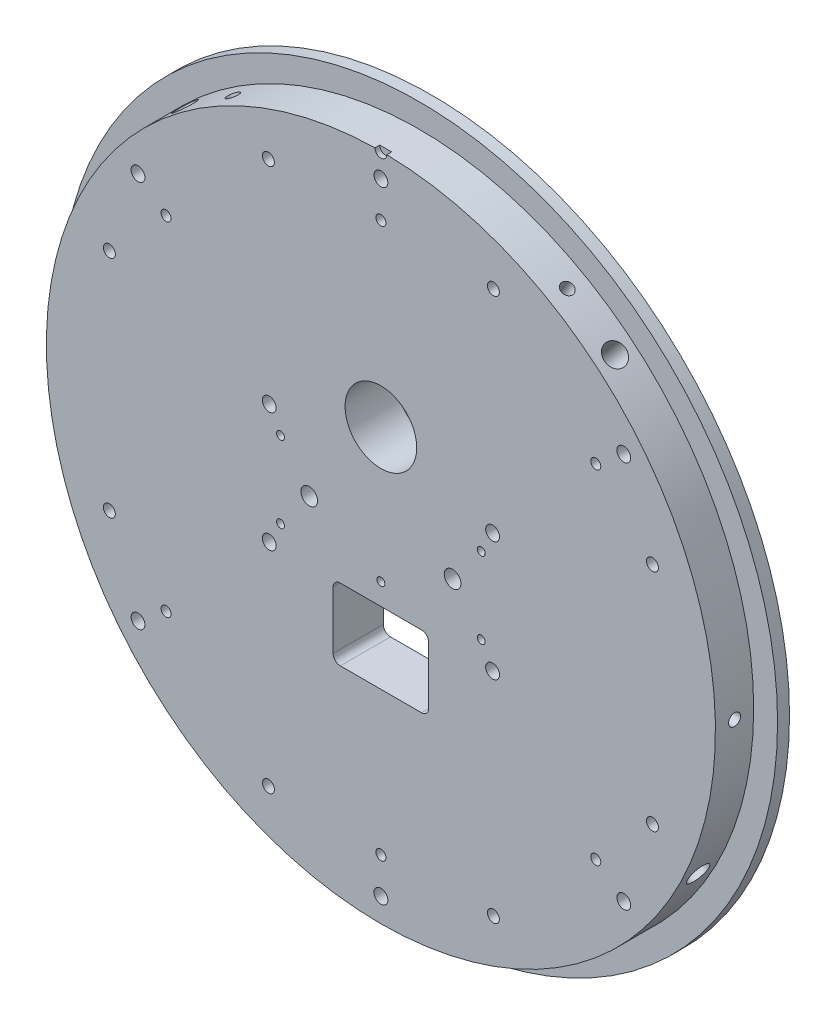
SolidWorks part; units mm, degrees
material "2017-T4"
ref_plane "正面" through (0, 0, 0) normal (0, 0, 1) x (1, 0, 0)
ref_plane "平面" through (0, 0, 0) normal (0, 1, 0) x (1, 0, 0)
ref_plane "右側面" through (0, 0, 0) normal (1, 0, 0) x (0, 0, -1)
ref_axis "中心軸" through (0, 0, -1.05) along (0, 0, 1)
sketch "ｽｹｯﾁ1" plane through (0, 0, 0) normal (0, 0, 1) x (1, 0, 0)
  circle A0 centre (0, 0) radius 150
  dimension "D1" = 300
extrude "ﾎﾞｽ - 押し出し1" add sketch "ｽｹｯﾁ1" along normal blind 5
sketch "ｽｹｯﾁ2" plane through (0, 0, 5) normal (0, 0, 1) x (1, 0, 0)
  circle A0 centre (0, 0) radius 140
  dimension "D1" = 280
extrude "ﾎﾞｽ - 押し出し2" add sketch "ｽｹｯﾁ2" along normal blind 16 contours A0
sketch "ｽｹｯﾁ3" plane through (0, 0, 0) normal (0, 0, -1) x (-1, 0, 0)
  line L1 (-20, -55) -> (20, -55)
  line L2 (-20, -55) -> (-20, -25)
  line L3 (-20, -25) -> (20, -25)
  line L4 (20, -55) -> (20, -25)
  line L5 (-20, -55) -> (20, -25) construction
  line L6 (-20, -25) -> (20, -55) construction
  circle A0 centre (0, 40) radius 15
  point P2 (0, -40)
  dimension "D1" = 30
  dimension "D2" = 40
  dimension "D3" = 40
  dimension "D4" = 30
  dimension "D5" = 55
extrude "ｶｯﾄ - 押し出し1" cut sketch "ｽｹｯﾁ3" against normal through all
fillet "ﾌｨﾚｯﾄ2" radius 3 4 edges at (20, -55, 10.5) (20, -25, 10.5) (-20, -25, 10.5) (-20, -55, 10.5)
sketch "ｽｹｯﾁ5" plane through (0, 0, 0) normal (0, 0, -1) x (-1, 0, 0)
  circle A0 centre (0, 0) radius 130
  point P3 (0, 130)
  point P4 (101.6401, 81.0511)
  point P5 (-101.6401, 81.0511)
  point P6 (-101.6401, -81.0511)
  point P7 (101.6401, -81.0511)
  point P8 (0, -130)
  dimension "D1" = 260
  dimension "D2" = 51.43
  dimension "D3" = 51.43
  dimension "D4" = 51.43
  dimension "D5" = 51.43
hole_wizard "M5 穴付きねじ用座ぐり穴1" positions "3Dｽｹｯﾁ1" profile "ｽｹｯﾁ4" counterbore size "M5" standard "JIS" end condition through all
sketch3d "3Dｽｹｯﾁ1"
  point P0 (0, 130, 0)
  point P2 (-101.6401, 81.0511, 0)
  point P4 (101.6401, 81.0511, 0)
  point P6 (101.6401, -81.0511, 0)
  point P8 (0, -130, 0)
  point P10 (-101.6401, -81.0511, 0)
sketch "ｽｹｯﾁ4" plane through (0, 130, 0) normal (1, 0, 0) x (0, 1, 0)
  line L0 (0, 0) -> (0, 21)
  line L1 (0, 21) -> (2.9, 21)
  line L3 (2.9, 21) -> (2.9, 8)
  line L4 (2.9, 8) -> (5, 8)
  line L5 (5, 8) -> (5, 0)
  line L7 (5, 0) -> (0, 0)
  line L11 (0, -6.35) -> (0, 107.95) construction
  dimension "通し穴の直径" = 5.8
  dimension "通し穴の深さ" = 21
  dimension "座ぐり穴の直径" = 10
  dimension "座ぐり穴の深さ" = 8
sketch "ｽｹｯﾁ7" plane through (0, 0, 0) normal (0, 0, -1) x (-1, 0, 0)
  point P0 (-30, 0)
  point P1 (30, 0)
  dimension "D1" = 30
  dimension "D2" = 30
hole_wizard "M6 穴付きねじ用座ぐり穴1" positions "3Dｽｹｯﾁ2" profile "ｽｹｯﾁ6" counterbore size "M6" standard "JIS" end condition through all
sketch3d "3Dｽｹｯﾁ2"
  point P0 (30, 0, 0)
  point P2 (-30, 0, 0)
sketch "ｽｹｯﾁ6" plane through (30, 0, 0) normal (1, 0, 0) x (0, 1, 0)
  line L0 (0, 0) -> (0, 21)
  line L1 (0, 21) -> (3.5, 21)
  line L3 (3.5, 21) -> (3.5, 9)
  line L4 (3.5, 9) -> (5.5, 9)
  line L5 (5.5, 9) -> (5.5, 0)
  line L7 (5.5, 0) -> (0, 0)
  line L11 (0, -6.35) -> (0, 107.95) construction
  dimension "通し穴の直径" = 7
  dimension "通し穴の深さ" = 21
  dimension "座ぐり穴の直径" = 11
  dimension "座ぐり穴の深さ" = 9
sketch "ｽｹｯﾁ8" plane through (0, 0, 0) normal (0, 0, -1) x (-1, 0, 0)
  line L1 (-46.7333, -25) -> (46.7333, -25) construction
  line L2 (-46.7333, -25) -> (-46.7333, 25) construction
  line L3 (-46.7333, 25) -> (46.7333, 25) construction
  line L4 (46.7333, -25) -> (46.7333, 25) construction
  line L5 (-46.7333, -25) -> (46.7333, 25) construction
  line L6 (-46.7333, 25) -> (46.7333, -25) construction
  point P0 (0, 0)
  dimension "D1" = 50
  dimension "D2" = 53
hole_wizard "M5 穴付きねじ用座ぐり穴2" positions "3Dｽｹｯﾁ3" profile "ｽｹｯﾁ9" counterbore size "M5" standard "JIS" end condition through all
sketch3d "3Dｽｹｯﾁ3"
  point P0 (46.7333, 25, 0)
  point P3 (46.7333, -25, 0)
  point P6 (-46.7333, 25, 0)
  point P9 (-46.7333, -25, 0)
sketch "ｽｹｯﾁ9" plane through (46.7333, 25, 0) normal (1, 0, 0) x (0, 1, 0)
  line L0 (0, 0) -> (0, 21)
  line L1 (0, 21) -> (2.9, 21)
  line L3 (2.9, 21) -> (2.9, 8)
  line L4 (2.9, 8) -> (5, 8)
  line L5 (5, 8) -> (5, 0)
  line L7 (5, 0) -> (0, 0)
  line L11 (0, -6.35) -> (0, 107.95) construction
  dimension "通し穴の直径" = 5.8
  dimension "通し穴の深さ" = 21
  dimension "座ぐり穴の直径" = 10
  dimension "座ぐり穴の深さ" = 8
sketch "ｽｹｯﾁ10" plane through (0, 0, 0) normal (0, 0, -1) x (-1, 0, 0)
  line L1 (-42, -16) -> (42, -16)
  line L2 (-42, -16) -> (-42, 16)
  line L3 (-42, 16) -> (42, 16)
  line L4 (42, -16) -> (42, 16)
  line L5 (-42, -16) -> (42, 16) construction
  line L6 (-42, 16) -> (42, -16) construction
  point P0 (0, 0)
  point P5 (0, -16)
  dimension "D1" = 84
  dimension "D2" = 32
hole_wizard "M4x0.7 ねじ穴1" positions "3Dｽｹｯﾁ4" profile "ｽｹｯﾁ11" tap size "M4x0.7" standard "JIS" end condition through all
sketch3d "3Dｽｹｯﾁ4"
  point P0 (42, 16, 0)
  point P3 (-42, 16, 0)
  point P6 (-42, -16, 0)
  point P9 (0, -16, 0)
  point P12 (42, -16, 0)
sketch "ｽｹｯﾁ11" plane through (42, 16, 0) normal (1, 0, 0) x (0, 1, 0)
  line L0 (0, 0) -> (0, 21)
  line L1 (0, 21) -> (1.65, 21)
  line L2 (1.65, 21) -> (1.65, 0)
  line L5 (1.65, 0) -> (0, 0)
  line L11 (0, -6.35) -> (0, 107.95) construction
  dimension "次ｻｰﾌｪｽまでのねじ下穴ﾄﾞﾘﾙ直径" = 3.3
  dimension "次ｻｰﾌｪｽまでのねじ下穴ﾄﾞﾘﾙの深さ" = 21
cosmetic thread "穴のねじ山1" parameters "D2"=4
cosmetic thread "穴のねじ山2" parameters "D2"=4
cosmetic thread "穴のねじ山3" parameters "D2"=4
cosmetic thread "穴のねじ山4" parameters "D2"=4
cosmetic thread "穴のねじ山5" parameters "D2"=4
sketch "ｽｹｯﾁ12" plane through (0, 0, 0) normal (0, 0, -1) x (-1, 0, 0)
  line L0 (0, 0) -> (212.6109, 0) construction
  line L1 (0, 0) -> (198.3068, 82.1414) construction
  point P3 (113.6372, 47.0701)
  dimension "D1" = 123
  dimension "D2" = 22.5
hole_wizard "M6x1.0 ねじ穴1" positions "3Dｽｹｯﾁ5" profile "ｽｹｯﾁ13" tap size "M6x1.0" standard "JIS" end condition through all
sketch3d "3Dｽｹｯﾁ5"
  point P0 (-113.6372, 47.0701, 0)
sketch "ｽｹｯﾁ13" plane through (-113.6372, 47.0701, 0) normal (1, 0, 0) x (0, 1, 0)
  line L0 (0, 0) -> (0, 21)
  line L1 (0, 21) -> (2.5, 21)
  line L2 (2.5, 21) -> (2.5, 0)
  line L5 (2.5, 0) -> (0, 0)
  line L11 (0, -6.35) -> (0, 107.95) construction
  dimension "次ｻｰﾌｪｽまでのねじ下穴ﾄﾞﾘﾙ直径" = 5
  dimension "次ｻｰﾌｪｽまでのねじ下穴ﾄﾞﾘﾙの深さ" = 21
cosmetic thread "穴のねじ山6" parameters "D2"=6
pattern_circular "円形ﾊﾟﾀｰﾝ1" count 8 over 360 about axis through (0, 0, 0) along (0, 0, 1) of "M6x1.0 ねじ穴1"
sketch "ｽｹｯﾁ14" plane through (0, 0, 21) normal (0, 0, -1) x (-1, 0, 0)
  circle A0 centre (0, 140) radius 2.5
  circle A2 centre (0, 0) radius 140 construction
  dimension "D1" = 5
extrude "ｶｯﾄ - 押し出し2" cut sketch "ｽｹｯﾁ14" along normal blind 2
sketch "ｽｹｯﾁ16" plane through (0, 0, 0) normal (0, 0, 1) x (1, 0, 0)
  circle A0 centre (0, 0) radius 115
  point P3 (0, 115)
  point P4 (89.9124, 71.6991)
  point P5 (-89.9124, 71.6991)
  point P6 (-89.9124, -71.6991)
  point P7 (89.9124, -71.6991)
  point P8 (0, -115)
  dimension "D1" = 230
  dimension "D2" = 51.43
  dimension "D3" = 51.43
  dimension "D4" = 51.43
  dimension "D5" = 51.43
hole_wizard "M5x0.8 ねじ穴1" positions "3Dｽｹｯﾁ6" profile "ｽｹｯﾁ17" tap size "M5x0.8" standard "JIS" end condition through all
sketch3d "3Dｽｹｯﾁ6"
  point P0 (-89.9124, 71.6991, 0)
  point P3 (-89.9124, 71.6991, 0)
  point P5 (-89.9124, -71.6991, 0)
  point P7 (0, -115, 0)
  point P9 (89.9124, -71.6991, 0)
  point P11 (89.9124, 71.6991, 0)
  point P13 (0, 115, 0)
sketch "ｽｹｯﾁ17" plane through (-89.9124, 71.6991, 0) normal (1, 0, 0) x (0, 1, 0)
  line L0 (0, 0) -> (0, 21)
  line L1 (0, 21) -> (2.1, 21)
  line L2 (2.1, 21) -> (2.1, 0)
  line L5 (2.1, 0) -> (0, 0)
  line L11 (0, -6.35) -> (0, 107.95) construction
  dimension "次ｻｰﾌｪｽまでのねじ下穴ﾄﾞﾘﾙ直径" = 4.2
  dimension "次ｻｰﾌｪｽまでのねじ下穴ﾄﾞﾘﾙの深さ" = 21
cosmetic thread "穴のねじ山7" parameters "D2"=5
cosmetic thread "穴のねじ山8" parameters "D2"=5
cosmetic thread "穴のねじ山9" parameters "D2"=5
cosmetic thread "穴のねじ山10" parameters "D2"=5
cosmetic thread "穴のねじ山11" parameters "D2"=5
cosmetic thread "穴のねじ山12" parameters "D2"=5
cosmetic thread "穴のねじ山13" parameters "D2"=5
ref_plane "平面1" through (0, 0, 13) normal (0, 0, 1) x (1, 0, 0)
sketch "ｽｹｯﾁ18" plane through (0, 0, 13) normal (0, 0, 1) x (1, 0, 0)
  circle A0 centre (0, 0) radius 140 construction
  circle A1 centre (0, 0) radius 140 construction
  point P0 (140, 0)
hole_wizard "M6x1.0 ねじ穴2" positions "3Dｽｹｯﾁ7" profile "ｽｹｯﾁ19" tap size "M6x1.0" standard "JIS"
sketch3d "3Dｽｹｯﾁ7"
  point P0 (140, 0, 13)
sketch "ｽｹｯﾁ19" plane through (140, 0, 13) normal (0, 1, 0) x (0, 0, -1)
  line L0 (0, 0) -> (0, 21.5022)
  line L1 (0, 21.5022) -> (2.5, 20)
  line L2 (2.5, 20) -> (2.5, 0)
  line L5 (2.5, 0) -> (0, 0)
  line L10 (0, 21.5022) -> (-2.5, 20) construction
  line L11 (0, -6.35) -> (0, 107.95) construction
  dimension "ねじ下穴ﾄﾞﾘﾙ直径" = 5
  dimension "ねじ下穴ﾄﾞﾘﾙの深さ" = 20
  dimension "ﾄﾞﾘﾙ角度" = 118
cosmetic thread "穴のねじ山14" parameters "D1"=12, "D2"=6
pattern_circular "円形ﾊﾟﾀｰﾝ2" count 6 over 360 about axis through (0, 0, -1.05) along (0, 0, 1) of "M6x1.0 ねじ穴2"
ref_plane "平面2" through (0, 0, 13) normal (0, 0, 1) x (1, 0, 0)
sketch "ｽｹｯﾁ20" plane through (0, 0, 13) normal (0, 0, 1) x (1, 0, 0)
  line L0 (0, 226.563) -> (0, -239.4482) construction
  line L1 (0, 0) -> (-89.9903, 107.2462) construction
  line L2 (0, 0) -> (89.9903, 107.2462) construction
  line L3 (0, 0) -> (124.7409, -63.5587) construction
  line L4 (0, 0) -> (-89.9903, -107.2462) construction
  circle A0 centre (0, 0) radius 140 construction
  arc A1 (-2.4999, 139.9777) -> (2.4999, 139.9777) centre (0, 0) ccw construction
  dimension "D1" = 40
  dimension "D2" = 40
  dimension "D3" = 63
  dimension "D4" = 40
hole_wizard "M10x1.0 ねじ穴1" positions "3Dｽｹｯﾁ8" profile "ｽｹｯﾁ21" tap size "M10x1.0" standard "JIS"
sketch3d "3Dｽｹｯﾁ8"
  point P0 (-89.9903, 107.2462, 13)
  point P2 (89.9903, 107.2462, 13)
  point P4 (124.7409, -63.5587, 13)
  point P6 (-89.9903, -107.2462, 13)
sketch "ｽｹｯﾁ21" plane through (-89.9903, 107.2462, 13) normal (0, 0, 1) x (-0.766, -0.6428, 0)
  line L0 (0, 0) -> (0, 27.7039)
  line L1 (0, 27.7039) -> (4.5, 25)
  line L2 (4.5, 25) -> (4.5, 0)
  line L5 (4.5, 0) -> (0, 0)
  line L10 (0, 27.7039) -> (-4.5, 25) construction
  line L11 (0, -6.35) -> (0, 107.95) construction
  dimension "ねじ下穴ﾄﾞﾘﾙ直径" = 9
  dimension "ねじ下穴ﾄﾞﾘﾙの深さ" = 25
  dimension "ﾄﾞﾘﾙ角度" = 118
cosmetic thread "穴のねじ山15" parameters "D1"=20, "D2"=10
cosmetic thread "穴のねじ山16" parameters "D1"=20, "D2"=10
cosmetic thread "穴のねじ山17" parameters "D1"=20, "D2"=10
cosmetic thread "穴のねじ山18" parameters "D1"=20, "D2"=10
